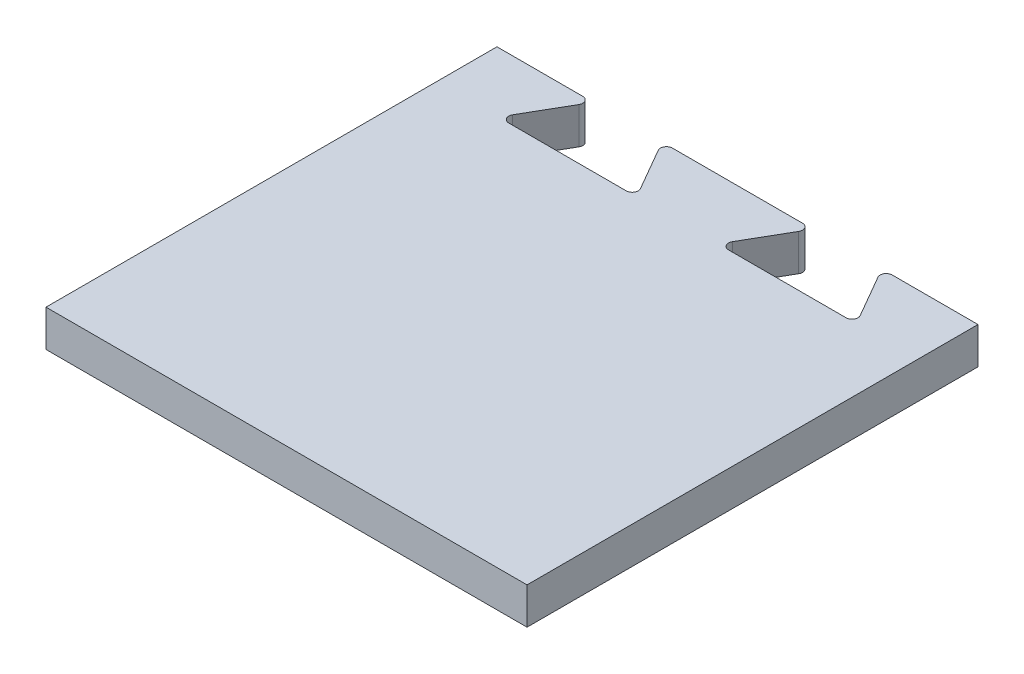
SolidWorks part; units mm, degrees
ref_plane "Front Plane" through (0, 0, 0) normal (0, 0, 1) x (1, 0, 0)
ref_plane "Top Plane" through (0, 0, 0) normal (0, 1, 0) x (1, 0, 0)
ref_plane "Right Plane" through (0, 0, 0) normal (1, 0, 0) x (0, 0, -1)
sketch "Sketch1" plane through (0, 0, 0) normal (0, 1, 0) x (1, 0, 0)
  line L0 (0, 0) -> (0, 37.5)
  line L1 (0, 37.5) -> (8, 37.5)
  line L2 (8, 37.5) -> (5.1132, 32.5)
  line L3 (5.1132, 32.5) -> (16.6132, 32.5)
  line L4 (16.6132, 32.5) -> (13.7265, 37.5)
  line L5 (13.7265, 37.5) -> (26.2735, 37.5)
  line L6 (26.2735, 37.5) -> (23.3868, 32.5)
  line L7 (23.3868, 32.5) -> (34.8868, 32.5)
  line L8 (34.8868, 32.5) -> (32, 37.5)
  line L9 (32, 37.5) -> (40, 37.5)
  line L10 (40, 37.5) -> (40, 0)
  line L11 (40, 0) -> (0, 0)
  dimension "D2" = 40
  dimension "D3" = 8
  dimension "D4" = 11.5
  dimension "D5" = 11.5
  dimension "D6" = 8
  dimension "D7" = 5
  dimension "D8" = 5
  dimension "D9" = 5
  dimension "D10" = 5
  dimension "D11" = 60
  dimension "D12" = 60
  dimension "D13" = 60
  dimension "D14" = 32.5
extrude "Boss-Extrude1" add sketch "Sketch1" along normal blind 3.05
fillet "Fillet3" radius 0.5 8 edges at (34.8868, 1.525, -32.5) (32, 1.525, -37.5) (23.3868, 1.525, -32.5) (26.2735, 1.525, -37.5) (13.7265, 1.525, -37.5) (16.6132, 1.525, -32.5) (5.1132, 1.525, -32.5) (8, 1.525, -37.5)
